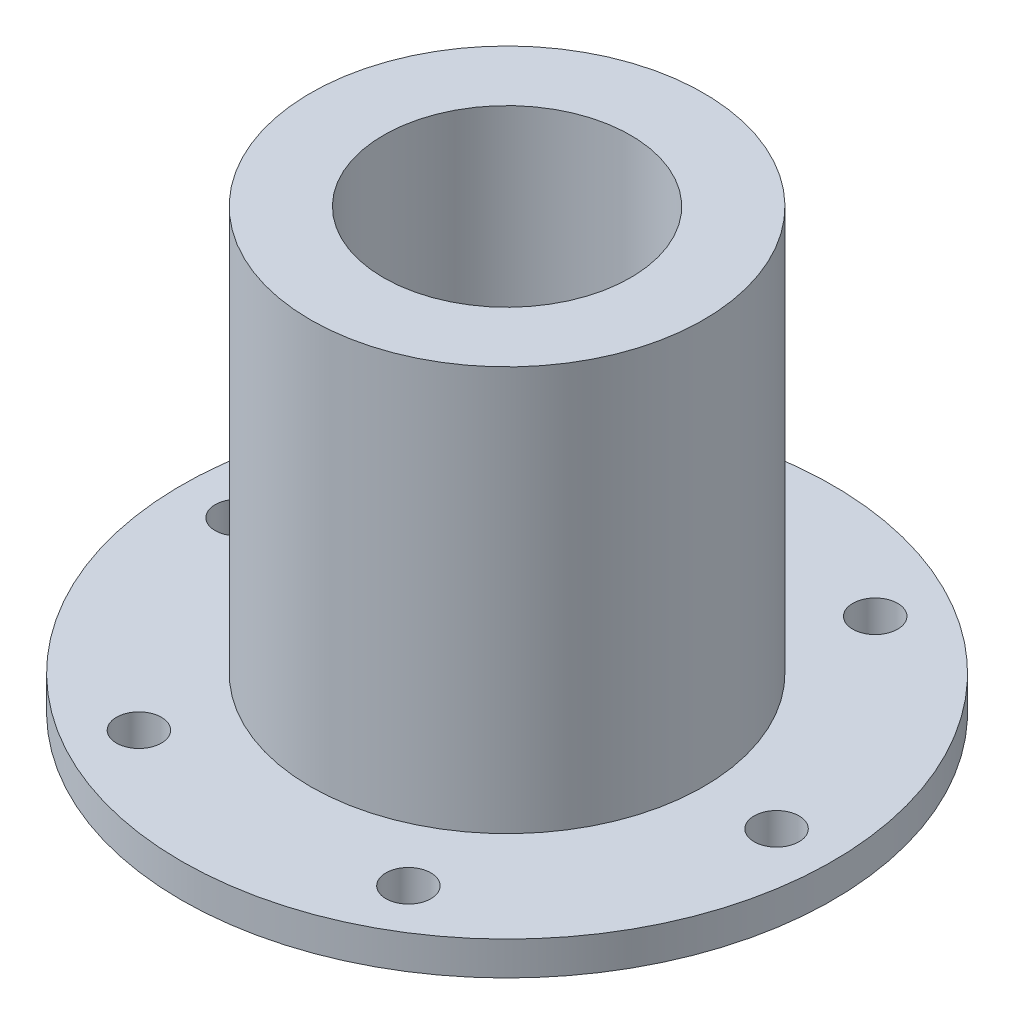
SolidWorks part; units mm, degrees
material "6061 合金"
ref_plane "前视基准面" through (0, 0, 0) normal (0, 0, 1) x (1, 0, 0)
ref_plane "上视基准面" through (0, 0, 0) normal (0, 1, 0) x (1, 0, 0)
ref_plane "右视基准面" through (0, 0, 0) normal (1, 0, 0) x (0, 0, -1)
other "Configuration Table"
sketch "草图1" plane through (0, 0, 0) normal (0, 1, 0) x (1, 0, 0)
  circle A0 centre (0, 0) radius 29
  dimension "D1" = 58
extrude "凸台-拉伸1" add sketch "草图1" along normal blind 3
sketch "草图3" plane through (0, 3, 0) normal (0, 1, 0) x (1, 0, 0)
  circle A0 centre (0, 0) radius 17.5
  dimension "D1" = 35
extrude "凸台-拉伸2" add sketch "草图3" along normal blind 36
sketch "草图4" plane through (0, 39, 0) normal (0, 1, 0) x (1, 0, 0)
  circle A0 centre (0, 0) radius 11
  dimension "D1" = 22
extrude "切除-拉伸2" cut sketch "草图4" against normal through all
sketch "草图5" plane through (0, 3, 0) normal (0, 1, 0) x (1, 0, 0)
  circle A0 centre (0, 0) radius 24 construction
  circle A1 centre (24, 0) radius 2
  circle A2 centre (12, -20.7846) radius 2
  circle A3 centre (-12, -20.7846) radius 2
  circle A4 centre (-24, 0) radius 2
  circle A5 centre (-12, 20.7846) radius 2
  circle A6 centre (12, 20.7846) radius 2
  dimension "D1" = 48
  dimension "D2" = 4
  dimension "D3" = 6
extrude "切除-拉伸3" cut sketch "草图5" against normal blind 10
